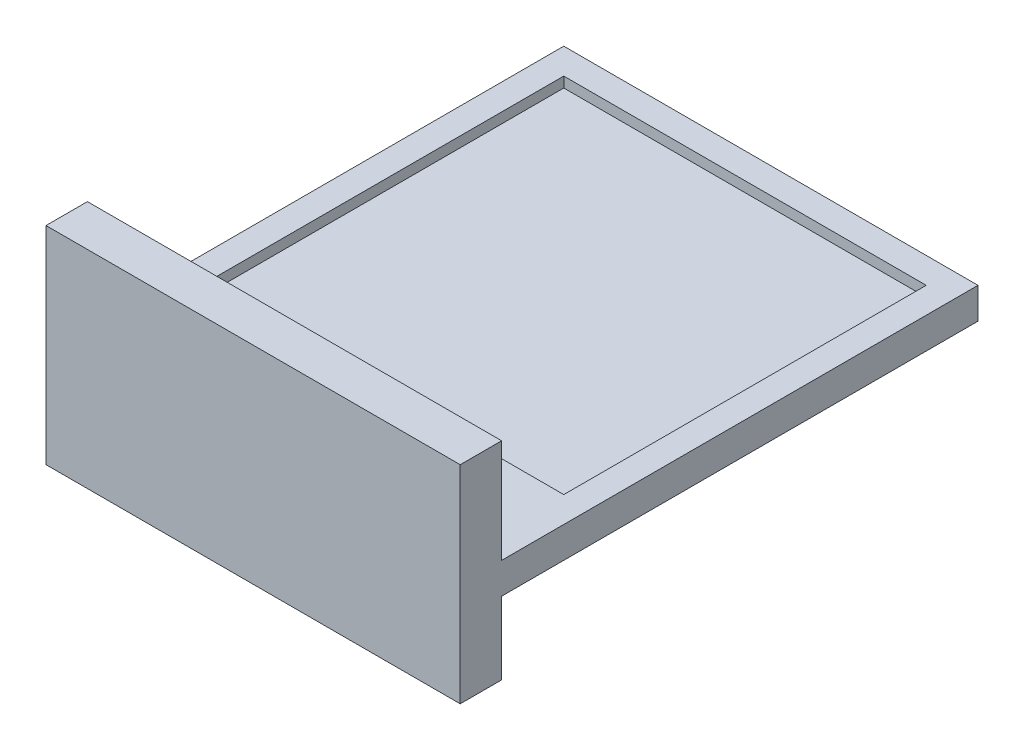
SolidWorks part; units mm, degrees
ref_plane "Front Plane" through (0, 0, 0) normal (0, 0, 1) x (1, 0, 0)
ref_plane "Top Plane" through (0, 0, 0) normal (0, 1, 0) x (1, 0, 0)
ref_plane "Right Plane" through (0, 0, 0) normal (1, 0, 0) x (0, 0, -1)
sketch "Sketch1" plane through (0, 0, 0) normal (0, 1, 0) x (1, 0, 0)
  line L1 (4, -5) -> (-4, -5)
  line L2 (4, -5) -> (4, 5)
  line L3 (4, 5) -> (-4, 5)
  line L4 (-4, -5) -> (-4, 5)
  line L5 (4, -5) -> (-4, 5) construction
  line L6 (4, 5) -> (-4, -5) construction
  point P0 (0, 0)
  dimension "D1" = 10
  dimension "D2" = 8
extrude "Boss-Extrude1" add sketch "Sketch1" along normal blind 0.6
sketch "Sketch4" plane through (0, 0.6, 0) normal (0, 1, 0) x (1, 0, 0)
  line L0 (4, -5) -> (4, 5) construction
  line L1 (-3.5, 4.5) -> (3.5, 4.5)
  line L2 (-3.5, 4.5) -> (-3.5, -2.5)
  line L3 (-3.5, -2.5) -> (3.5, -2.5)
  line L4 (3.5, 4.5) -> (3.5, -2.5)
  line L5 (4, 5) -> (-4, 5) construction
  dimension "D1" = 7
  dimension "D2" = 7
  dimension "D3" = 0.5
  dimension "D4" = 0.5
extrude "Cut-Extrude1" cut sketch "Sketch4" against normal blind 0.4
sketch "Sketch5" plane through (0, 0, -5) normal (0, 0, -1) x (-1, 0, 0)
  line L1 (-3.7, 0.4) -> (3.7, 0.4)
  line L2 (-3.7, 0.4) -> (-3.7, 0.2)
  line L3 (-3.7, 0.2) -> (3.7, 0.2)
  line L4 (3.7, 0.4) -> (3.7, 0.2)
  line L5 (-4, 0.6) -> (4, 0.6) construction
  line L6 (4, 0.6) -> (4, 0) construction
  line L7 (-4, 0.6) -> (-4, 0) construction
  dimension "D1" = 0.2
  dimension "D2" = 0.2
  dimension "D3" = 0.3
  dimension "D4" = 0.3
extrude "Cut-Extrude2" cut sketch "Sketch5" against normal blind 8 contours L1 L4 L3 L2
sketch "Sketch6" plane through (0, 0.6, 0) normal (0, 1, 0) x (1, 0, 0)
  line L0 (-4, -5) -> (4, -5) construction
  line L1 (-4, -5) -> (4, -5)
  line L2 (-4, -5) -> (-4, -4.2)
  line L3 (-4, -4.2) -> (4, -4.2)
  line L4 (4, -5) -> (4, -4.2)
  line L5 (-4, 5) -> (-4, -5) construction
  line L6 (4, -5) -> (4, 5) construction
  dimension "D1" = 0.8
extrude "Boss-Extrude2" add sketch "Sketch6" along normal blind 2 and the other way blind 2
